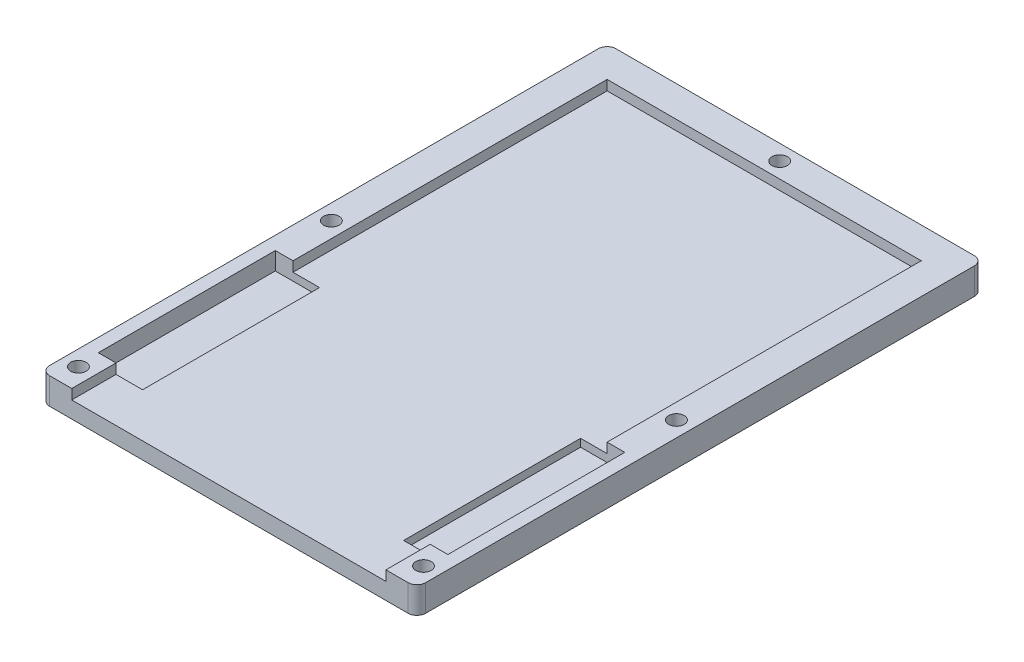
SolidWorks part; units mm, degrees
ref_plane "Front Plane" through (0, 0, 0) normal (0, 0, 1) x (1, 0, 0)
ref_plane "Top Plane" through (0, 0, 0) normal (0, 1, 0) x (1, 0, 0)
ref_plane "Right Plane" through (0, 0, 0) normal (1, 0, 0) x (0, 0, -1)
sketch "Sketch1" plane through (0, 0, 0) normal (0, 1, 0) x (1, 0, 0)
  line L1 (42.5, -64) -> (-42.5, -64)
  line L2 (42.5, -64) -> (42.5, 64)
  line L3 (42.5, 64) -> (-42.5, 64)
  line L4 (-42.5, -64) -> (-42.5, 64)
  line L5 (42.5, -64) -> (-42.5, 64) construction
  line L6 (42.5, 64) -> (-42.5, -64) construction
  point P0 (0, 0)
  dimension "D1" = 85
  dimension "D2" = 128
extrude "Top Lid" add sketch "Sketch1" along normal blind 6
sketch "Sketch2" plane through (0, 0, 0) normal (0, -1, 0) x (1, 0, 0)
  line L0 (42.5, 64) -> (42.5, -64) construction
  line L1 (-42.5, 64) -> (42.5, 64) construction
  line L2 (-42.5, -64) -> (-42.5, 64) construction
  line L3 (42.5, -64) -> (-42.5, -64) construction
  circle A0 centre (39, 59) radius 1.75
  circle A1 centre (-39, 59) radius 1.75
  circle A2 centre (-39, 1.83) radius 1.75
  circle A3 centre (39, 1.83) radius 1.75
  circle A4 centre (0, -60.5) radius 1.75
  dimension "D1" = 3.5
  dimension "D6" = 3.5
  dimension "D2" = 3.5
  dimension "D3" = 5
  dimension "D4" = 3.5
  dimension "D5" = 57.17
extrude "Screw Hole" cut sketch "Sketch2" against normal blind 10
sketch "Sketch5" plane through (0, 0, 0) normal (0, -1, 0) x (1, 0, 0)
  circle A0 centre (39, 59) radius 2.5
  circle A1 centre (-39, 59) radius 2.5
  circle A2 centre (-39, 1.83) radius 2.5
  circle A3 centre (39, 1.83) radius 2.5
  circle A4 centre (0, -60.5) radius 2.5
  dimension "D1" = 5
extrude "Screw Head" cut sketch "Sketch5" against normal blind 2 draft 45
sketch "Sketch6" plane through (0, 6, 0) normal (0, 1, 0) x (1, 0, 0)
  line L0 (-42.5, -64) -> (42.5, -64) construction
  line L1 (-35.5, -64) -> (35.5, -64)
  line L2 (-35.5, -64) -> (-35.5, 57)
  line L3 (-35.5, 57) -> (35.5, 57)
  line L4 (35.5, -64) -> (35.5, 57)
  line L5 (0, -52.9641) -> (0, -64) construction
  line L6 (42.5, 64) -> (-42.5, 64) construction
  dimension "D1" = 71
  dimension "D2" = 7
extrude "Device cut out" cut sketch "Sketch6" against normal blind 2.25
sketch "Sketch7" plane through (0, 6, 0) normal (0, 1, 0) x (1, 0, 0)
  line L0 (35.5, -64) -> (42.5, -64) construction
  line L1 (39.5, -54) -> (29.5, -54)
  line L2 (39.5, -54) -> (39.5, -14)
  line L3 (39.5, -14) -> (29.5, -14)
  line L4 (29.5, -54) -> (29.5, -14)
  line L5 (42.5, -64) -> (42.5, 64) construction
  line L6 (0, 57) -> (0, -73.3875) construction
  line L7 (35.5, 57) -> (-35.5, 57) construction
  line L8 (-39.5, -54) -> (-29.5, -54)
  line L9 (-39.5, -54) -> (-39.5, -14)
  line L10 (-29.5, -54) -> (-29.5, -14)
  line L11 (-39.5, -14) -> (-29.5, -14)
  dimension "D1" = 40
  dimension "D2" = 10
  dimension "D3" = 10
  dimension "D4" = 3
extrude "Sliders" cut sketch "Sketch7" against normal blind 4
fillet "Fillet1" radius 2 1 edges at (42.5, 3, 64)
fillet "Fillet2" radius 2 1 edges at (42.5, 3, -64)
fillet "Fillet3" radius 2 1 edges at (-42.5, 3, -64)
fillet "Fillet4" radius 2 1 edges at (-42.5, 3, 64)
equation "\"wall_thickness\"= 3mm"
equation "\"D1@Sketch1\"=\"case_width\""
equation "\"c_outside_width\"= 70mm"
equation "\"case_length\"= \"wall_thickness\" + 125mm"
equation "\"D2@Sketch1\"=\"case_length\""
equation "\"inner_lip\"= \"wall_thickness\" + 0.5mm"
equation "\"case_width\"= \"c_outside_width\" + ( \"wall_thickness\" * 2 ) + 9"
